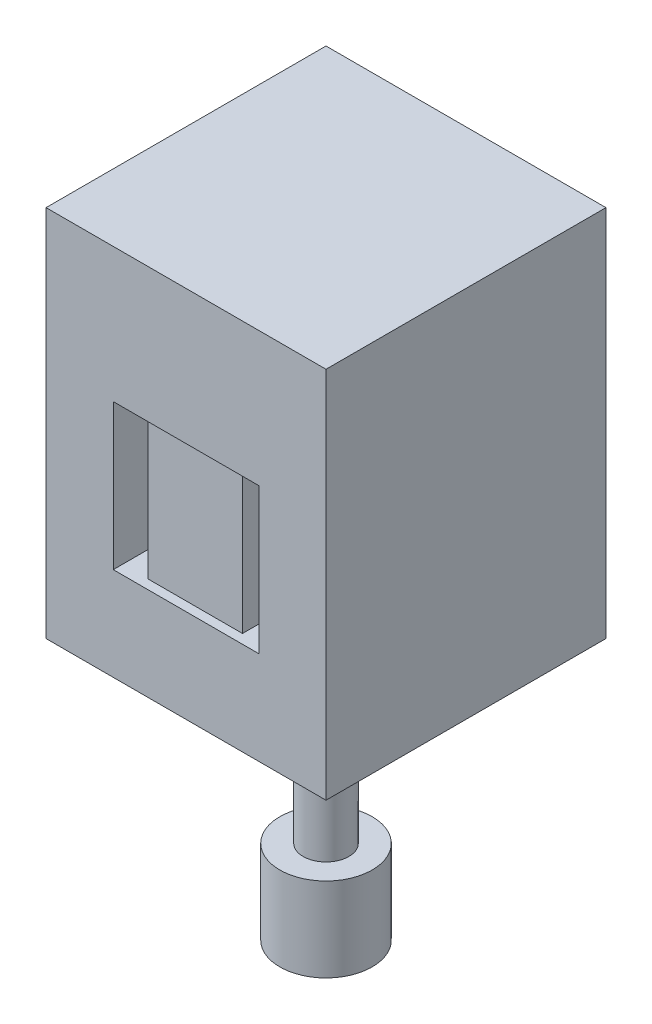
SolidWorks part; units mm, degrees
ref_plane "前视基准面" through (0, 0, 0) normal (0, 0, 1) x (1, 0, 0)
ref_plane "上视基准面" through (0, 0, 0) normal (0, 1, 0) x (1, 0, 0)
ref_plane "右视基准面" through (0, 0, 0) normal (1, 0, 0) x (0, 0, -1)
other "Configuration Table"
sketch "草图1" plane through (0, 0, 0) normal (0, 1, 0) x (1, 0, 0)
  line L1 (-15, -15) -> (15, -15)
  line L2 (-15, -15) -> (-15, 15)
  line L3 (-15, 15) -> (15, 15)
  line L4 (15, -15) -> (15, 15)
  line L5 (-15, -15) -> (15, 15) construction
  line L6 (-15, 15) -> (15, -15) construction
  point P0 (0, 0)
  point P6 (15, 9.1317)
  dimension "D1" = 30
  dimension "D2" = 30
extrude "凸台-拉伸1" add sketch "草图1" along normal blind 40
sketch "草图2" plane through (0, 0, 0) normal (0, -1, 0) x (1, 0, 0)
  circle A0 centre (0, 0) radius 2.45
  dimension "D1" = 4.9
extrude "凸台-拉伸2" add sketch "草图2" along normal blind 19
sketch "草图3" plane through (0, -19, 0) normal (0, -1, 0) x (1, 0, 0)
  circle A0 centre (0, 0) radius 4.95
  dimension "D1" = 9.9
extrude "凸台-拉伸3" add sketch "草图3" along normal blind 9
sketch "草图4" plane through (0, 0, 15) normal (0, 0, 1) x (1, 0, 0)
  line L1 (-7.8, 10) -> (7.8, 10)
  line L2 (-7.8, 10) -> (-7.8, 25.6)
  line L3 (-7.8, 25.6) -> (7.8, 25.6)
  line L4 (7.8, 10) -> (7.8, 25.6)
  line L5 (-7.8, 10) -> (7.8, 25.6) construction
  line L6 (-7.8, 25.6) -> (7.8, 10) construction
  point P0 (0, 17.8)
  dimension "D1" = 15.6
  dimension "D2" = 15.6
  dimension "D3" = 10
extrude "切除-拉伸1" cut sketch "草图4" against normal blind 1
sketch "草图5" plane through (0, 0, 14) normal (0, 0, 1) x (1, 0, 0)
  line L0 (-7.8, 10) -> (7.8, 10) construction
  line L1 (-7.8, 25.6) -> (-5.05, 25.6)
  line L2 (-7.8, 25.6) -> (-7.8, 10)
  line L3 (-7.8, 10) -> (-5.05, 10)
  line L4 (-5.05, 25.6) -> (-5.05, 10)
  line L5 (-7.8, 10) -> (7.8, 10) construction
  line L6 (7.8, 25.6) -> (5.05, 25.6)
  line L7 (7.8, 25.6) -> (7.8, 10)
  line L8 (7.8, 10) -> (5.05, 10)
  line L9 (5.05, 25.6) -> (5.05, 10)
  dimension "D1" = 10.1
extrude "切除-拉伸2" cut sketch "草图5" against normal blind 3
fillet "圆角1" radius 3 1 edges at (0, 0, -2.45)
